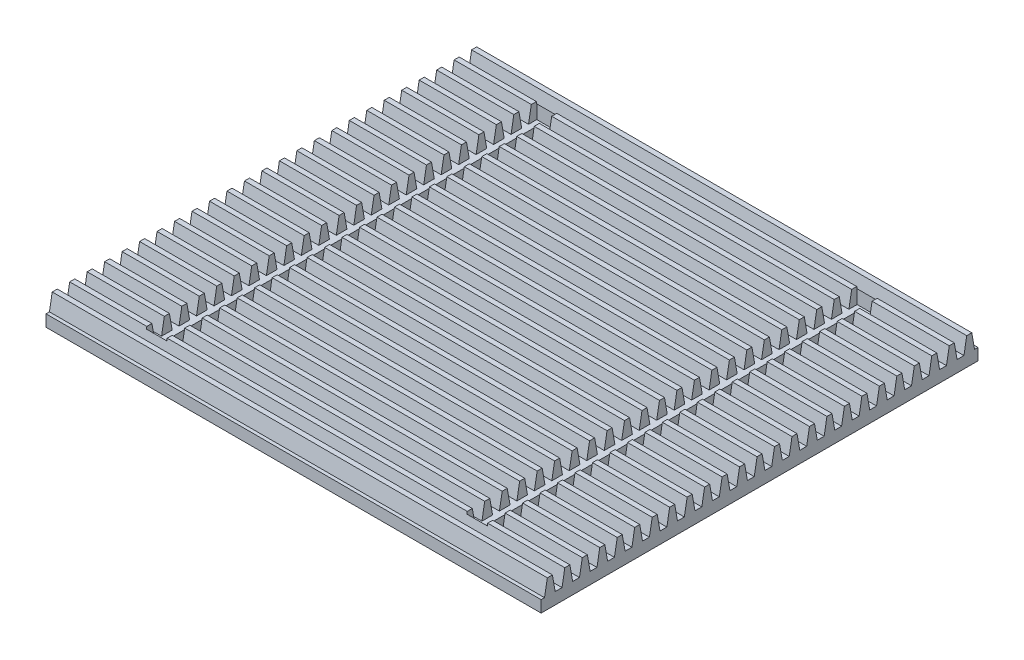
SolidWorks part; units mm, degrees
ref_plane "Front Plane" through (0, 0, 0) normal (0, 0, 1) x (1, 0, 0)
ref_plane "Top Plane" through (0, 0, 0) normal (0, 1, 0) x (1, 0, 0)
ref_plane "Right Plane" through (0, 0, 0) normal (1, 0, 0) x (0, 0, -1)
sketch "Sketch1" plane through (0, 0, 0) normal (1, 0, 0) x (0, 0, -1)
  line L0 (0, 0) -> (6, 0)
  line L1 (6, 0) -> (6, 4)
  line L2 (0, 4) -> (1.1735, 4)
  line L3 (1.1735, 4) -> (2.1317, 9.434)
  line L4 (2.1317, 9.434) -> (3.8683, 9.434)
  line L5 (0, 0) -> (0, 4)
  line L6 (3.8683, 9.434) -> (4.8265, 4)
  line L7 (4.8265, 4) -> (6, 4)
  dimension "D1" = 6
  dimension "D2" = 4
  dimension "D3" = 100
  dimension "D4" = 100
extrude "Boss-Extrude1" add sketch "Sketch1" along normal blind 170
pattern_linear "LPattern1" count 25 spacing 6 along (0, 0, -1) of "Boss-Extrude1"
sketch "Sketch2" plane through (0, 0, 0) normal (0, -1, 0) x (1, 0, 0)
  line L0 (0, 0) -> (0, -150) construction
  line L1 (28.5, -10) -> (31.5, -10)
  line L2 (28.5, -10) -> (28.5, -140)
  line L3 (28.5, -140) -> (31.5, -140)
  line L4 (31.5, -10) -> (31.5, -140)
  line L5 (170, 0) -> (0, 0) construction
  line L6 (170, -150) -> (0, -150) construction
  dimension "D1" = 3
  dimension "D2" = 28.5
  dimension "D3" = 10
  dimension "D4" = 10
extrude "Cut-Extrude1" cut sketch "Sketch2" against normal blind 10
sketch "Sketch3" plane through (0, 4, 0) normal (0, 1, 0) x (1, 0, 0)
  line L1 (33.5, 142) -> (26.5, 142)
  line L2 (33.5, 142) -> (33.5, 8)
  line L3 (33.5, 8) -> (26.5, 8)
  line L4 (26.5, 142) -> (26.5, 8)
  line L7 (28.5, 140) -> (31.5, 140) construction
  line L8 (31.5, 10) -> (28.5, 10) construction
  line L9 (31.5, 13.1735) -> (31.5, 10.8265) construction
  line L10 (28.5, 10.8265) -> (28.5, 13.1735) construction
  dimension "D1" = 2
  dimension "D2" = 2
  dimension "D3" = 2
  dimension "D4" = 2
extrude "Cut-Extrude3" cut sketch "Sketch3" along normal up to surface (5.434 mm away) up to face at (100.75, 9.434, -63)
ref_plane "Plane1" through (85, 0, 0) normal (1, 0, 0) x (0, 0, -1)
mirror "Mirror1" about plane through (85, 0, 0) normal (1, 0, 0) of "Cut-Extrude3", "Cut-Extrude1"
